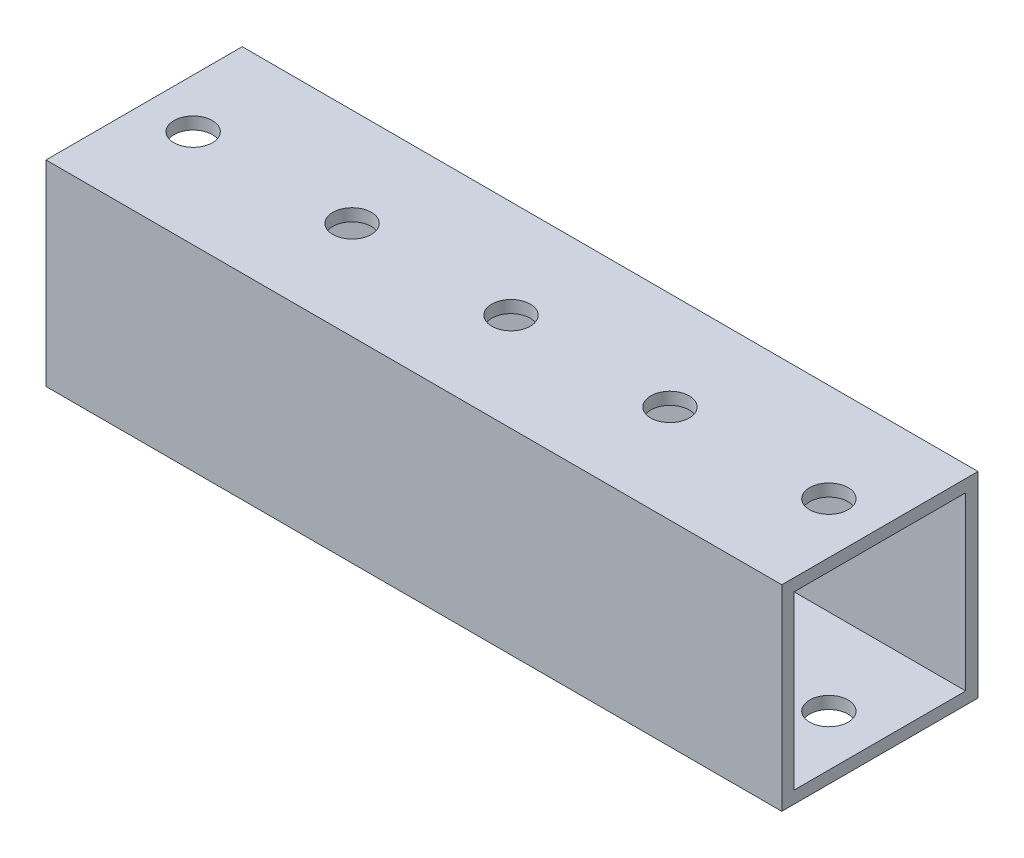
SolidWorks part; units mm, degrees
ref_plane "Front Plane" through (0, 0, 0) normal (0, 0, 1) x (1, 0, 0)
ref_plane "Top Plane" through (0, 0, 0) normal (0, 1, 0) x (1, 0, 0)
ref_plane "Right Plane" through (0, 0, 0) normal (1, 0, 0) x (0, 0, -1)
sketch "Sketch1" plane through (0, 0, 0) normal (1, 0, 0) x (0, 0, -1)
  line L0 (1.5875, 23.8125) -> (23.8125, 23.8125)
  line L1 (0, 0) -> (25.4, 0)
  line L2 (0, 0) -> (0, 25.4)
  line L3 (0, 25.4) -> (25.4, 25.4)
  line L4 (25.4, 0) -> (25.4, 25.4)
  line L5 (23.8125, 1.5875) -> (23.8125, 23.8125)
  line L6 (1.5875, 1.5875) -> (23.8125, 1.5875)
  line L7 (1.5875, 1.5875) -> (1.5875, 23.8125)
  dimension "D1" = 25.4
  dimension "D2" = 25.4
  dimension "D3" = 1.5875
extrude "Boss-Extrude1" add sketch "Sketch1" along normal blind 95.25
sketch "Sketch2" plane through (0, 25.4, 0) normal (0, 1, 0) x (1, 0, 0)
  line L0 (0, 25.4) -> (0, 0) construction
  line L1 (95.25, 0) -> (0, 0) construction
  line L2 (6.35, 12.7) -> (26.924, 12.7) construction
  circle A0 centre (6.35, 12.7) radius 2.4892
  circle A1 centre (26.924, 12.7) radius 2.4892
  circle A2 centre (47.498, 12.7) radius 2.4892
  circle A3 centre (68.072, 12.7) radius 2.4892
  circle A4 centre (88.646, 12.7) radius 2.4892
  dimension "D1" = 4.9784
  dimension "D2" = 6.35
  dimension "D3" = 12.7
  dimension "D5" = 20.574
  dimension "D4" = 5
extrude "Cut-Extrude1" cut sketch "Sketch2" against normal blind 95.25
